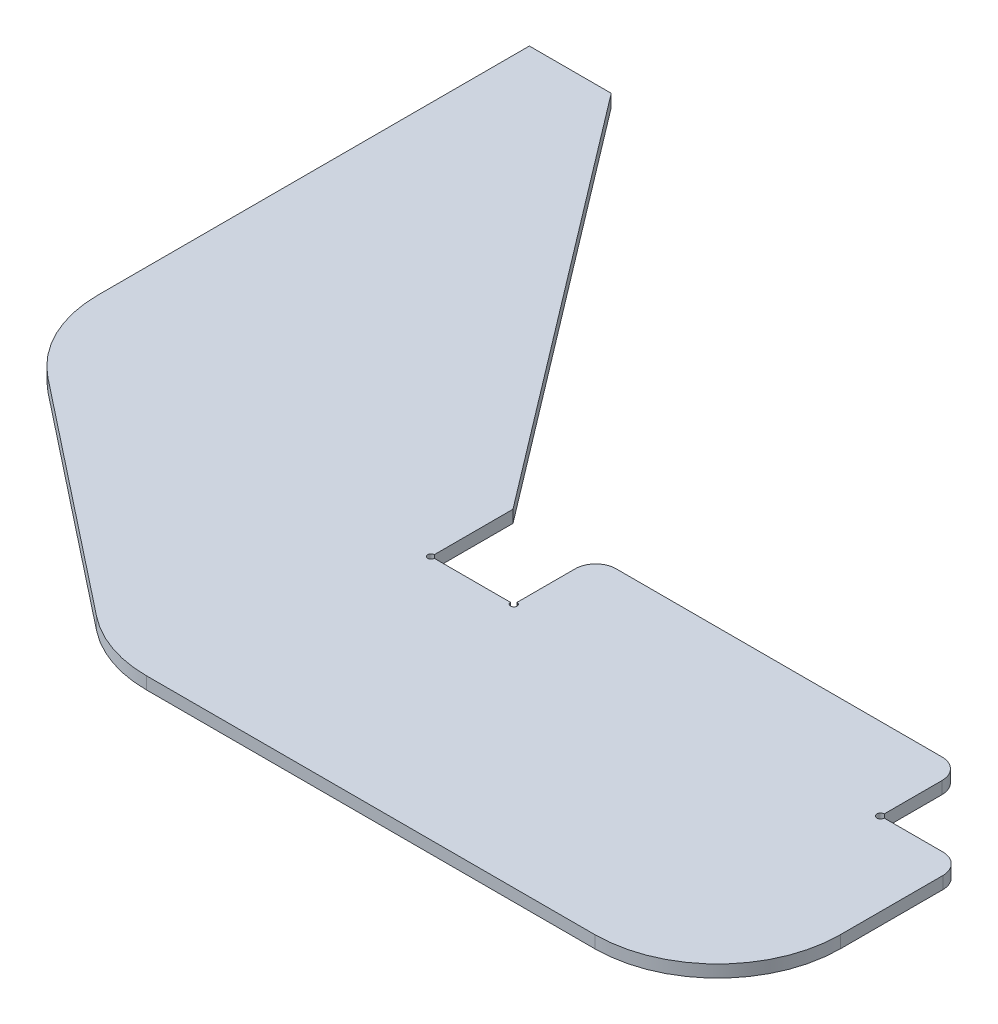
SolidWorks part; units mm, degrees
material "Thornel Mat VMA"
ref_plane "Front Plane" through (0, 0, 0) normal (0, 0, 1) x (1, 0, 0)
ref_plane "Top Plane" through (0, 0, 0) normal (0, 1, 0) x (1, 0, 0)
ref_plane "Right Plane" through (0, 0, 0) normal (1, 0, 0) x (0, 0, -1)
sketch "Sketch1" plane through (0, 0, 0) normal (0, 1, 0) x (1, 0, 0)
  line L1 (-75, -30) -> (75, -30)
  line L2 (-75, -30) -> (-75, 30)
  line L3 (-75, 30) -> (75, 30)
  line L4 (75, -30) -> (75, 30)
  line L5 (-75, -30) -> (75, 30) construction
  line L6 (-75, 30) -> (75, -30) construction
  point P0 (0, 0)
  dimension "D1" = 60
  dimension "D2" = 150
extrude "Boss-Extrude1" add sketch "Sketch1" along normal blind 3
fillet "Fillet1" radius 30 1 edges at (75, 1.5, 30)
sketch "Sketch2" plane through (0, 3, 0) normal (0, 1, 0) x (1, 0, 0)
  line L0 (75, 30) -> (-75, 30) construction
  line L1 (54.8, 30) -> (-34.8, 30)
  line L2 (54.8, 30) -> (54.8, 50)
  line L3 (54.8, 50) -> (-34.8, 50)
  line L4 (-34.8, 30) -> (-34.8, 50)
  line L5 (75, 0) -> (75, 30) construction
  line L6 (-151, 30) -> (-75, -30)
  line L7 (-55, 30) -> (-151, 30)
  line L8 (-55, 30) -> (-55, 50)
  line L9 (-55, 50) -> (-151, 50)
  line L10 (-151, 30) -> (-151, 50)
  line L11 (-75, -30) -> (-75, 30)
  line M11 (75, 30) -> (-75, 30)
  line M12 (-75, 30) -> (-75, -30)
  dimension "D1" = 89.6
  dimension "D2" = 20.2
  dimension "D3" = 20
  dimension "D4" = 20.2
  dimension "D5" = 76
extrude "Boss-Extrude2" add sketch "Sketch2" against normal up to surface (3 mm away) contours L10 L7 L8 L9 M11 | L7 L6 M12 | L4 L2 L3 M11 up to face at (10.2426, 0, 1.2426)
fillet "Fillet2" radius 30 2 edges at (-75, 1.5, 30) (-151, 1.5, -30)
sketch "Sketch3" plane through (0, 3, 0) normal (0, 1, 0) x (1, 0, 0)
  circle A0 centre (-55, 30) radius 0.8
  circle A1 centre (-34.8, 30) radius 0.8
  circle A2 centre (54.8, 30) radius 0.8994
  dimension "D1" = 1.6
extrude "Cut-Extrude1" cut sketch "Sketch3" against normal through all
fillet "Fillet3" radius 5 3 edges at (75, 1.5, -30) (54.8, 1.5, -50) (-34.8, 1.5, -50)
sketch "Sketch4" plane through (0, 0, 0) normal (0, -1, 0) x (-1, 0, 0)
  line L1 (151, 50) -> (131, 50)
  line L2 (151, 50) -> (151, 150)
  line L3 (151, 150) -> (131, 150)
  line L4 (131, 50) -> (131, 150)
  point P7 (0, 0)
  dimension "D1" = 20
  dimension "D2" = 100
extrude "Boss-Extrude3" add sketch "Sketch4" against normal up to surface (3 mm away) up to face at (-20.2766, 3, -25.0241)
sketch "Sketch5" plane through (0, 3, 0) normal (0, 1, 0) x (1, 0, 0)
  line L0 (-131, 150) -> (-55, 50)
  line L1 (-55, 50) -> (-131, 50)
  line L2 (-131, 50) -> (-131, 150)
extrude "Boss-Extrude4" add sketch "Sketch5" against normal up to surface (3 mm away) up to face at (-30.3424, 0, -36.3855)
